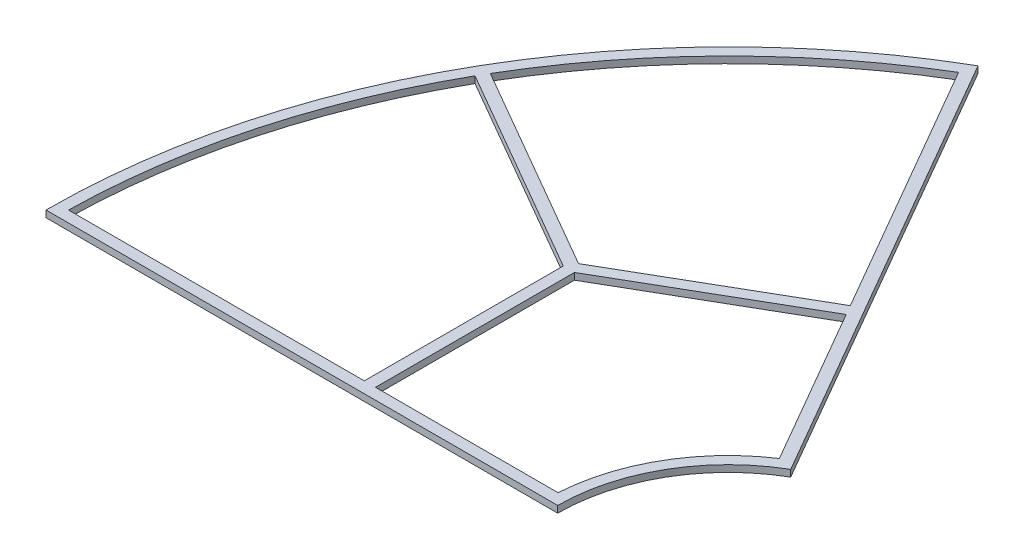
SolidWorks part; units mm, degrees
ref_plane "Front Plane" through (0, 0, 0) normal (0, 0, 1) x (1, 0, 0)
ref_plane "Top Plane" through (0, 0, 0) normal (0, 1, 0) x (1, 0, 0)
ref_plane "Right Plane" through (0, 0, 0) normal (1, 0, 0) x (0, 0, -1)
sketch "Sketch1" plane through (0, 0, 0) normal (0, 1, 0) x (1, 0, 0)
  line L0 (-152.4, 0) -> (-609.6, 0)
  line L1 (-76.2, 131.9823) -> (-304.8, 527.9291)
  line L2 (-530.4113, 300.4596) -> (-530.4291, 300.4699)
  line L3 (-525.4113, 309.1199) -> (-525.4291, 309.1301)
  line L4 (-330.2, 196.4146) -> (-516.7508, 304.1197)
  line L5 (-89.7062, 135.3756) -> (-171.2603, 276.6315)
  line L6 (-162.0918, 10) -> (-325.2, 10)
  line L7 (-176.2603, 285.2917) -> (-308.4186, 514.1966)
  line L8 (-325.2, 10) -> (-325.2, 187.7543)
  line L9 (-325.2, 187.7543) -> (-171.2603, 276.6315)
  line L10 (-335.2, 10) -> (-599.5166, 10)
  line L11 (-335.2, 10) -> (-335.2, 187.7543)
  line L12 (-330.2, 196.4146) -> (-176.2603, 285.2917)
  line L13 (-335.2, 187.7543) -> (-521.7508, 295.4594)
  line L14 (-89.7062, 135.3756) -> (-308.4186, 514.1966) construction
  line L16 (-162.0918, 10) -> (-599.5166, 10) construction
  arc A0 (-609.6, 0) -> (-304.8, 527.9291) centre (0, 0) cw
  arc A1 (-76.2, 131.9823) -> (-152.4, 0) centre (0, 0) ccw
  arc A2 (-599.5166, 10) -> (-521.7508, 295.4594) centre (0, 0) cw
  arc A3 (-89.7062, 135.3756) -> (-162.0918, 10) centre (0, 0) ccw
  arc A4 (-516.7508, 304.1197) -> (-308.4186, 514.1966) centre (0, 0) cw
  arc A6 (-599.5166, 10) -> (-308.4186, 514.1966) centre (0, 0) cw construction
  point P5 (-330.2, 0)
  point P7 (0, 0)
  point P9 (-165.1, 285.9616)
  dimension "D3" = 330.2
  dimension "D1" = 609.6
  dimension "D4" = 330.2
  dimension "D5" = 10
  dimension "D6" = 60
  dimension "D2" = 2
extrude "Boss-Extrude3" add sketch "Sketch1" along normal blind 6 contours A1 L1 A0 L0 L10 A2 L13 L11 L5 A3 L6 L8 L9 L4 A4 L7 L12
